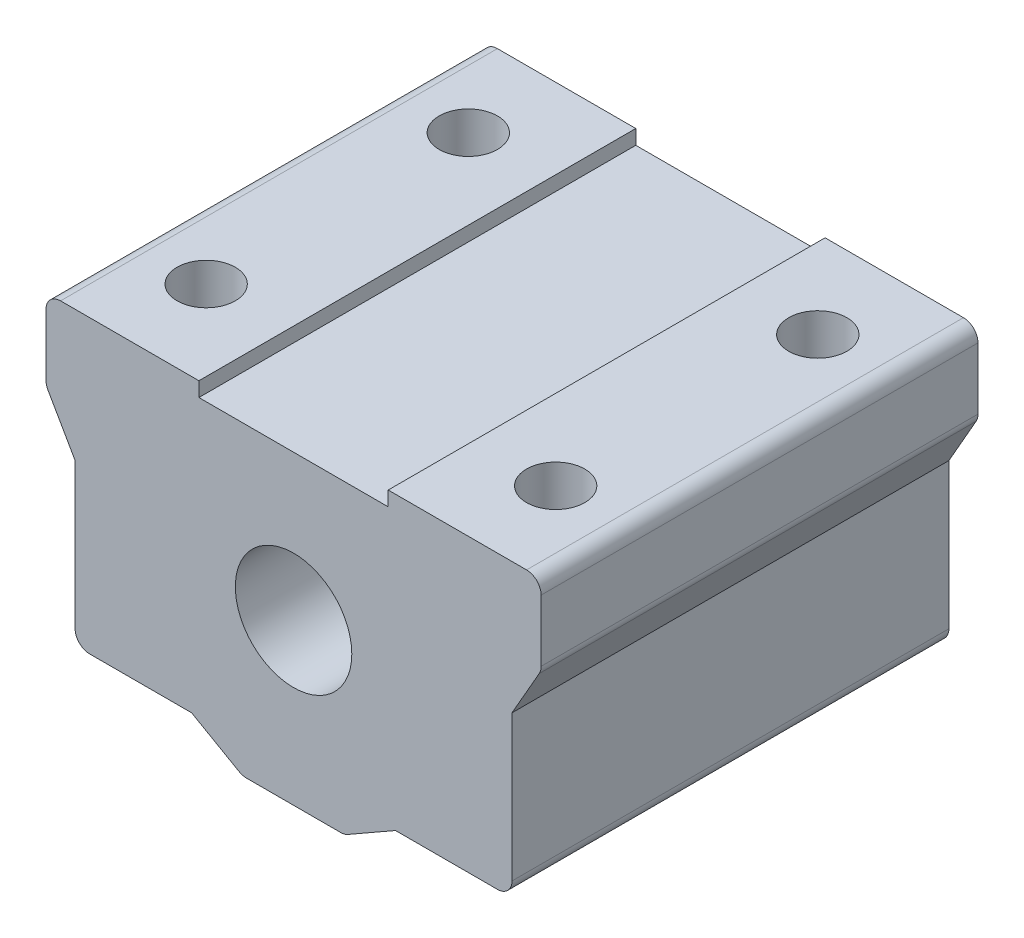
SolidWorks part; units mm, degrees
ref_plane "Front Plane" through (0, 0, 0) normal (0, 0, 1) x (1, 0, 0)
ref_plane "Top Plane" through (0, 0, 0) normal (0, 1, 0) x (1, 0, 0)
ref_plane "Right Plane" through (0, 0, 0) normal (1, 0, 0) x (0, 0, -1)
sketch "Sketch1" plane through (0, 0, 0) normal (0, 0, 1) x (1, 0, 0)
  line L0 (0, 10.3825) -> (0, -12.3551) construction
  line L1 (-17, 0) -> (17, 0)
  line L2 (-21.1106, -22) -> (29.4029, -22) construction
  line L3 (17, 0) -> (17, -5.5)
  line L4 (17, -5.5) -> (15, -9)
  line L5 (15, -9) -> (15, -20)
  line L6 (15, -20) -> (7, -20)
  line L7 (7, -20) -> (3.5, -22)
  line L8 (3.5, -22) -> (-3.5, -22)
  line L9 (-3.5, -22) -> (-7, -20)
  line L10 (-7, -20) -> (-15, -20)
  line L11 (-15, -20) -> (-15, -9)
  line L12 (-15, -9) -> (-17, -5.5)
  line L13 (-17, -5.5) -> (-17, 0)
  point P5 (0, 0)
  dimension "D1" = 34
  dimension "D2" = 22
  dimension "D3" = 5.5
  dimension "D4" = 2
  dimension "D5" = 11
  dimension "D6" = 8
  dimension "D7" = 7
extrude "Boss-Extrude1" add sketch "Sketch1" along normal blind 30
fillet "Fillet1" radius 1 8 edges at (3.5, -22, 15) (15, -20, 15) (17, -5.5, 15) (17, 0, 15) (-3.5, -22, 15) (-15, -20, 15) (-17, -5.5, 15) (-17, 0, 15)
sketch "Sketch2" plane through (0, 0, 30) normal (0, 0, 1) x (1, 0, 0)
  line L0 (0, 5.3914) -> (0, -29.8946) construction
  line L1 (16, 0) -> (-16, 0) construction
  circle A0 centre (0, -11) radius 4
  dimension "D1" = 8
  dimension "D2" = 11
extrude "Cut-Extrude1" cut sketch "Sketch2" against normal up to next
sketch "Sketch3" plane through (0, 0, 0) normal (0, 1, 0) x (1, 0, 0)
  line L0 (0, -25.8738) -> (0, -37.8738) construction
  line L1 (12, 5.4687) -> (12, -35.8375) construction
  line L2 (-12, 5.4687) -> (-12, -36.6673) construction
  line L3 (-23.7751, -6) -> (24.4727, -6) construction
  line L4 (16, 0) -> (-16, 0) construction
  line L5 (-23.2416, -24) -> (23.9392, -24) construction
  line L6 (16, -30) -> (-16, -30) construction
  line L7 (17, 0) -> (17, -30) construction
  line L8 (-17, -30) -> (-17, 0) construction
  circle A0 centre (-12, -6) radius 2
  circle A1 centre (-12, -24) radius 2
  circle A2 centre (12, -24) radius 2
  circle A3 centre (12, -6) radius 2
  dimension "D5" = 4
  dimension "D1" = 12
  dimension "D2" = 12
  dimension "D3" = 6
  dimension "D4" = 6
extrude "Cut-Extrude2" cut sketch "Sketch3" against normal up to next
sketch "Sketch4" plane through (0, 0, 0) normal (0, 1, 0) x (1, 0, 0)
  line L0 (16, 0) -> (-16, 0) construction
  line L1 (-6.5, 0) -> (6.5, 0)
  line L2 (-6.5, 0) -> (-6.5, -30)
  line L3 (-6.5, -30) -> (6.5, -30)
  line L4 (6.5, 0) -> (6.5, -30)
  line L5 (16, -30) -> (-16, -30) construction
  dimension "D1" = 6.5
  dimension "D2" = 6.5
extrude "Cut-Extrude3" cut sketch "Sketch4" against normal blind 1
